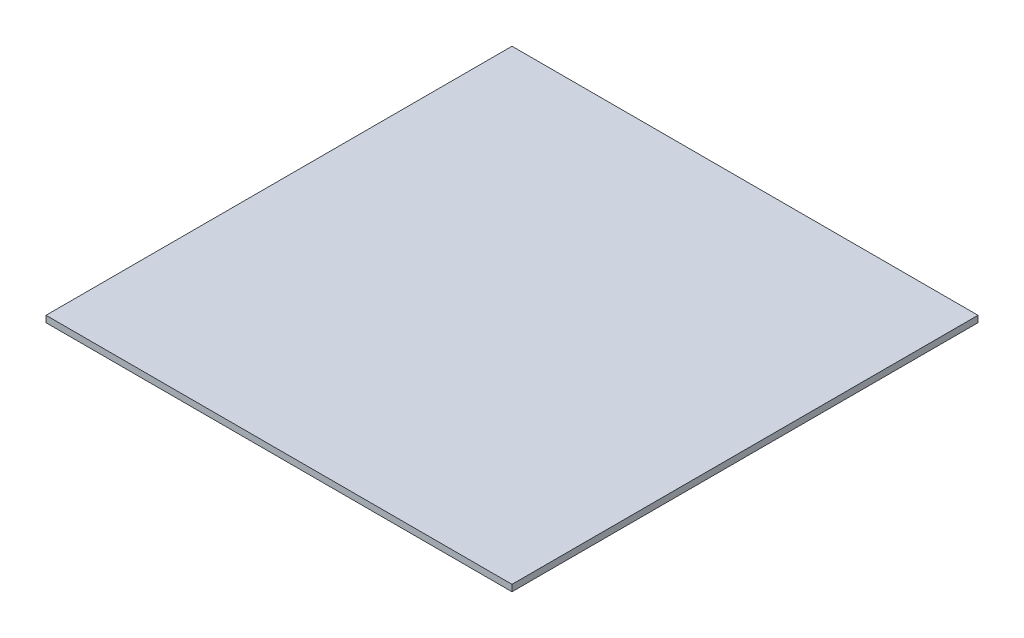
SolidWorks part; units mm, degrees
material "Teak"
ref_plane "Front Plane" through (0, 0, 0) normal (0, 0, 1) x (1, 0, 0)
ref_plane "Top Plane" through (0, 0, 0) normal (0, 1, 0) x (1, 0, 0)
ref_plane "Right Plane" through (0, 0, 0) normal (1, 0, 0) x (0, 0, -1)
sketch "Sketch1" plane through (0, 0, 0) normal (0, 1, 0) x (1, 0, 0)
  line L1 (-900, 900) -> (900, 900)
  line L2 (-900, 900) -> (-900, -900)
  line L3 (-900, -900) -> (900, -900)
  line L4 (900, 900) -> (900, -900)
  line L5 (-900, 900) -> (900, -900) construction
  line L6 (-900, -900) -> (900, 900) construction
  point P0 (0, 0)
  point P5 (0, 0)
  dimension "D1" = 1800
extrude "Boss-Extrude1" add sketch "Sketch1" along normal blind 25
